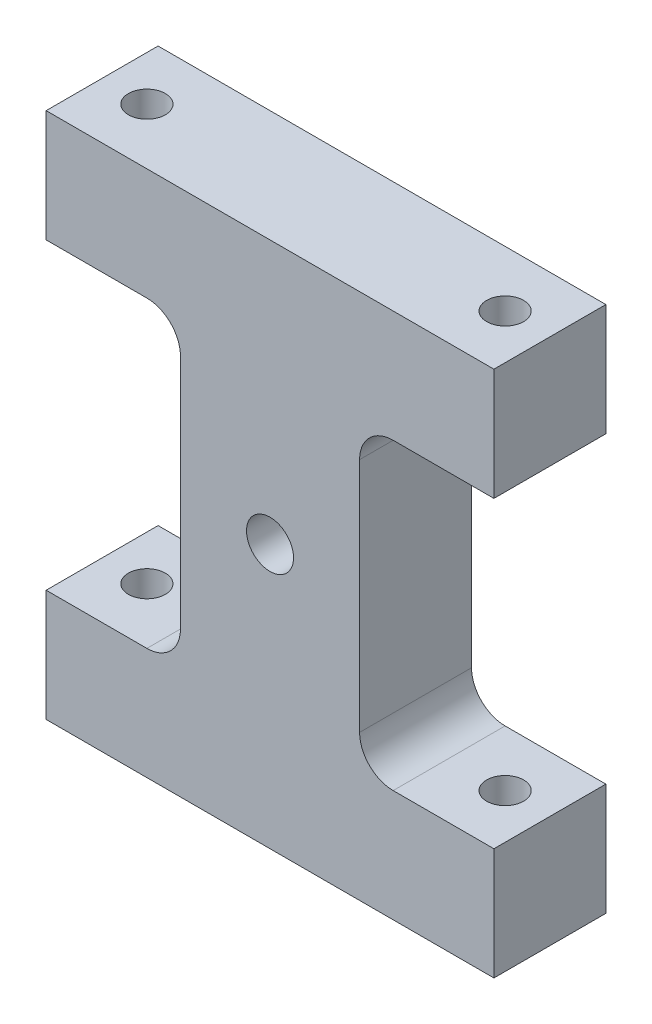
SolidWorks part; units mm, degrees
material "6061 合金"
ref_plane "前视基准面" through (0, 0, 0) normal (0, 0, 1) x (1, 0, 0)
ref_plane "上视基准面" through (0, 0, 0) normal (0, 1, 0) x (1, 0, 0)
ref_plane "右视基准面" through (0, 0, 0) normal (1, 0, 0) x (0, 0, -1)
other "Configuration Table"
sketch "草图1" plane through (0, 0, 0) normal (0, 0, 1) x (1, 0, 0)
  line L1 (-20, -23.55) -> (20, -23.55)
  line L2 (-20, -23.55) -> (-20, 23.55)
  line L3 (-20, 23.55) -> (20, 23.55)
  line L4 (20, -23.55) -> (20, 23.55)
  line L5 (-20, -23.55) -> (20, 23.55) construction
  line L6 (-20, 23.55) -> (20, -23.55) construction
  point P0 (0, 0)
  dimension "D1" = 47.1
  dimension "D2" = 40
extrude "凸台-拉伸1" add sketch "草图1" along normal blind 10
sketch "草图2" plane through (0, 23.55, 0) normal (0, 1, 0) x (1, 0, 0)
  line L0 (0, 0) -> (0, -10) construction
  line L1 (20, -10) -> (-20, -10) construction
  line L2 (-16, -5) -> (16, -5) construction
  point P8 (0, -5)
  dimension "D1" = 32
hole_wizard "M4 螺纹孔1" positions "草图3" profile "草图4" tap size "M4" standard "GB"
sketch "草图3" plane through (0, 23.55, 0) normal (0, 1, 0) x (1, 0, 0)
  point P0 (-16, -5)
  point P3 (16, -5)
sketch "草图4" plane through (-16, 23.55, 5) normal (1, 0, 0) x (0, 0, 1)
  line L0 (0, 0) -> (0, 11.0914)
  line L1 (0, 11.0914) -> (1.65, 10.1)
  line L2 (1.65, 10.1) -> (1.65, 0)
  line L5 (1.65, 0) -> (0, 0)
  line L10 (0, 11.0914) -> (-1.65, 10.1) construction
  line L11 (0, -6.35) -> (0, 107.95) construction
  dimension "螺纹孔钻头直径" = 3.3
  dimension "螺纹孔钻头深度" = 10.1
  dimension "导头角度" = 118
cosmetic thread "孔螺蚊线1" parameters "D1"=8, "D2"=4
cosmetic thread "孔螺蚊线2" parameters "D1"=8, "D2"=4
mirror "镜向1" about plane through (0, 0, 0) normal (0, 1, 0) of "M4 螺纹孔1"
hole_wizard "M5 螺纹孔1" positions "草图6" profile "草图7" tap size "M5" standard "GB"
sketch "草图6" plane through (0, 0, 10) normal (0, 0, 1) x (1, 0, 0)
  point P0 (0, 0)
sketch "草图7" plane through (0, 0, 10) normal (1, 0, 0) x (0, -1, 0)
  line L0 (0, 0) -> (0, 13.6618)
  line L1 (0, 13.6618) -> (2.1, 12.4)
  line L2 (2.1, 12.4) -> (2.1, 0)
  line L5 (2.1, 0) -> (0, 0)
  line L10 (0, 13.6618) -> (-2.1, 12.4) construction
  line L11 (0, -6.35) -> (0, 107.95) construction
  dimension "螺纹孔钻头直径" = 4.2
  dimension "螺纹孔钻头深度" = 12.4
  dimension "导头角度" = 118
cosmetic thread "孔螺蚊线3" parameters "D1"=10, "D2"=5
sketch "草图8" plane through (0, 0, 10) normal (0, 0, 1) x (1, 0, 0)
  line L0 (20, -23.55) -> (20, 23.55) construction
  line L1 (8, -13.55) -> (32, -13.55)
  line L2 (8, -13.55) -> (8, 13.55)
  line L3 (8, 13.55) -> (32, 13.55)
  line L4 (32, -13.55) -> (32, 13.55)
  line L5 (8, -13.55) -> (32, 13.55) construction
  line L6 (8, 13.55) -> (32, -13.55) construction
  line L7 (20, 23.55) -> (-20, 23.55) construction
  point P0 (20, 0)
  dimension "D1" = 8
  dimension "D2" = 10
extrude "切除-拉伸1" cut sketch "草图8" against normal up to surface (10 mm away) up to face at (-2.1, 0, 0)
mirror "镜向2" about plane through (0, 0, 0) normal (1, 0, 0) of "切除-拉伸1"
fillet "圆角1" radius 3 4 edges at (8, -13.55, 5) (8, 13.55, 5) (-8, 13.55, 5) (-8, -13.55, 5)
